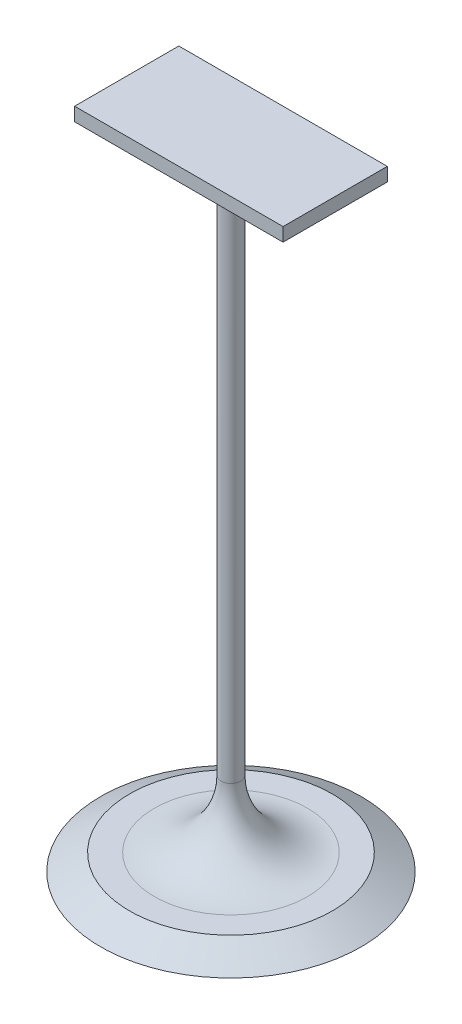
SolidWorks part; units mm, degrees
ref_plane "Piano frontale" through (0, 0, 0) normal (0, 0, 1) x (1, 0, 0)
ref_plane "Piano superiore" through (0, 0, 0) normal (0, 1, 0) x (1, 0, 0)
ref_plane "Piano destro" through (0, 0, 0) normal (1, 0, 0) x (0, 0, -1)
sketch "Schizzo4" plane through (0, 0, 0) normal (0, 0, 1) x (1, 0, 0)
  line L0 (0, 0) -> (-12.5, 0)
  line L1 (-12.5, 0) -> (-9.7287, 1.6)
  line L2 (-9.7287, 1.6) -> (-0.95, 1.6)
  line L4 (-0.95, 8) -> (-0.95, 1.6)
  line L5 (0, 0) -> (0, 59.8)
  line L6 (-0.95, 59.8) -> (0, 59.8)
  line L8 (-0.95, 8) -> (-0.95, 59.8)
  line L13 (0, -7.3571) -> (0, 95.6779) construction
  dimension "D1" = 150
  dimension "D2" = 1.6
  dimension "D3" = 12.5
  dimension "D5" = 51.8
revolve "Rivoluzione9" add sketch "Schizzo4" angle 360 about L13
fillet "Raccordo2" radius 6.4 1 edges at (0, 1.6, -0.95)
sketch "Schizzo5" plane through (0, 59.8, 0) normal (0, 1, 0) x (1, 0, 0)
  line L1 (-10, 5) -> (10, 5)
  line L2 (-10, 5) -> (-10, -5)
  line L3 (-10, -5) -> (10, -5)
  line L4 (10, 5) -> (10, -5)
  line L5 (-10, 5) -> (10, -5) construction
  line L6 (-10, -5) -> (10, 5) construction
  point P1 (0, 0)
  dimension "D1" = 20
  dimension "D2" = 10
extrude "Estrusione-Estrusione1" add sketch "Schizzo5" along normal blind 1.3
